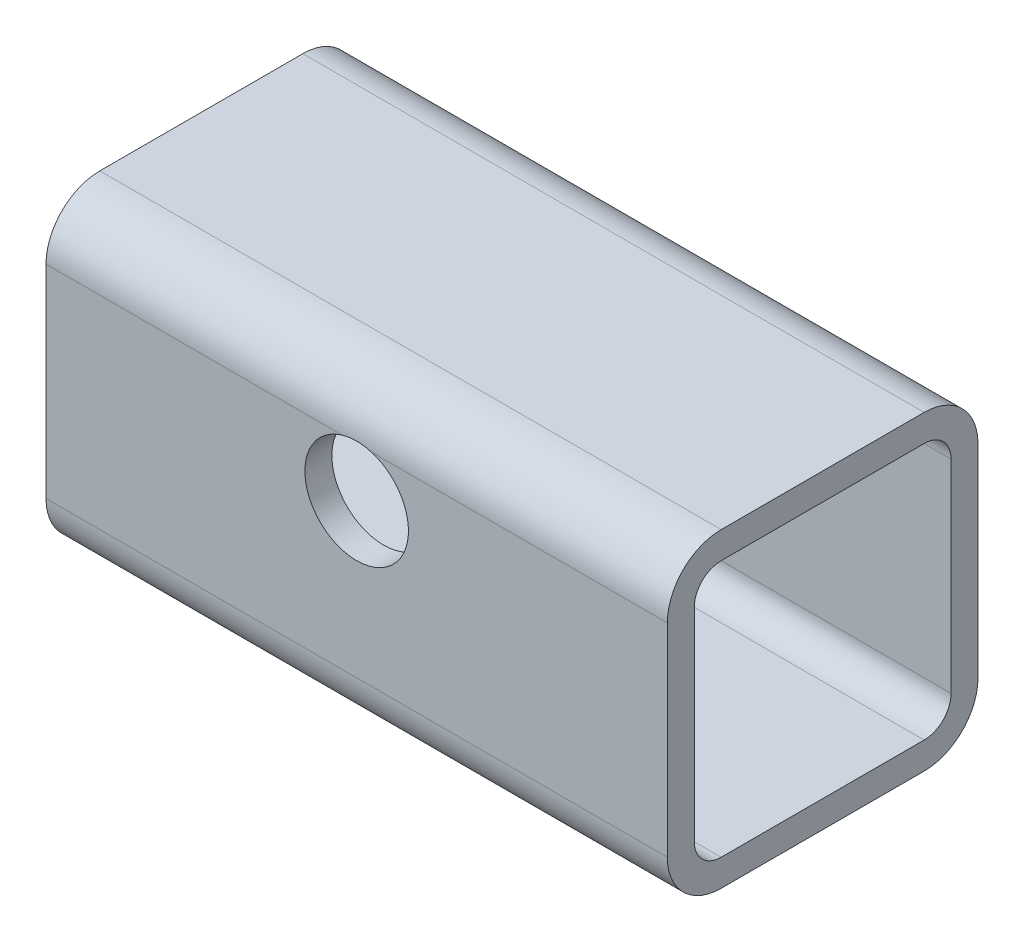
SolidWorks part; units mm, degrees
ref_plane "Płaszczyzna przednia" through (0, 0, 0) normal (0, 0, 1) x (1, 0, 0)
ref_plane "Płaszczyzna górna" through (0, 0, 0) normal (0, 1, 0) x (1, 0, 0)
ref_plane "Płaszczyzna prawa" through (0, 0, 0) normal (1, 0, 0) x (0, 0, -1)
sketch3d "Szkic 3D1"
  line L0 (0, 0, 0) -> (60, 0, 0)
  dimension "D1" = 60
other "Rura kwadratowa 30 X 30 X 2.6(1)"
ref_plane "Płaszczyzna1" through (0, 0, 0) normal (1, 0, 0) x (0, 0, -1)
sketch "Sketch11" plane through (0, 0, 0) normal (1, 0, 0) x (0, 0, -1)
  line L0 (-9.8, -12.4) -> (9.8, -12.4)
  line L1 (-12.4, -9.8) -> (-12.4, 9.8)
  line L2 (9.8, 12.4) -> (-9.8, 12.4)
  line L3 (12.4, 9.8) -> (12.4, -9.8)
  line L4 (-9.8, -15) -> (9.8, -15)
  line L5 (-15, -9.8) -> (-15, 9.8)
  line L6 (9.8, 15) -> (-9.8, 15)
  line L7 (15, 9.8) -> (15, -9.8)
  arc A0 (15, 9.8) -> (9.8, 15) centre (9.8, 9.8) ccw
  arc A1 (9.8, -15) -> (15, -9.8) centre (9.8, -9.8) ccw
  arc A2 (-15, -9.8) -> (-9.8, -15) centre (-9.8, -9.8) ccw
  arc A3 (-9.8, 15) -> (-15, 9.8) centre (-9.8, 9.8) ccw
  arc A4 (-9.8, 12.4) -> (-12.4, 9.8) centre (-9.8, 9.8) ccw
  arc A5 (12.4, 9.8) -> (9.8, 12.4) centre (9.8, 9.8) ccw
  arc A6 (9.8, -12.4) -> (12.4, -9.8) centre (9.8, -9.8) ccw
  arc A7 (-12.4, -9.8) -> (-9.8, -12.4) centre (-9.8, -9.8) ccw
  point P0 (-15, 0)
  point P1 (15, 0)
  point P2 (0, 15)
  point P3 (0, -15)
  point P4 (0, 0)
  point P5 (-15, -15)
  point P6 (15, -15)
  point P7 (15, 15)
  point P8 (-15, 15)
  point P33 (0, 0)
  dimension "D1" = 5.2
  dimension "Thickness" = 2.6
  dimension "V_leg" = 30
sketch "Szkic3" plane through (0, 0, 15) normal (0, 0, 1) x (1, 0, 0)
  line L0 (30, 28.5653) -> (30, -28.7455) construction
  line L1 (60, 9.8) -> (60, -9.8) construction
  line L2 (0, 9.8) -> (0, -9.8) construction
  line L5 (60, 15) -> (0, 15) construction
  circle A0 centre (30, 5) radius 5
  dimension "D1" = 10
  dimension "D2" = 10
extrude "Wytnij-wyciągnięcie1" cut sketch "Szkic3" against normal through all
